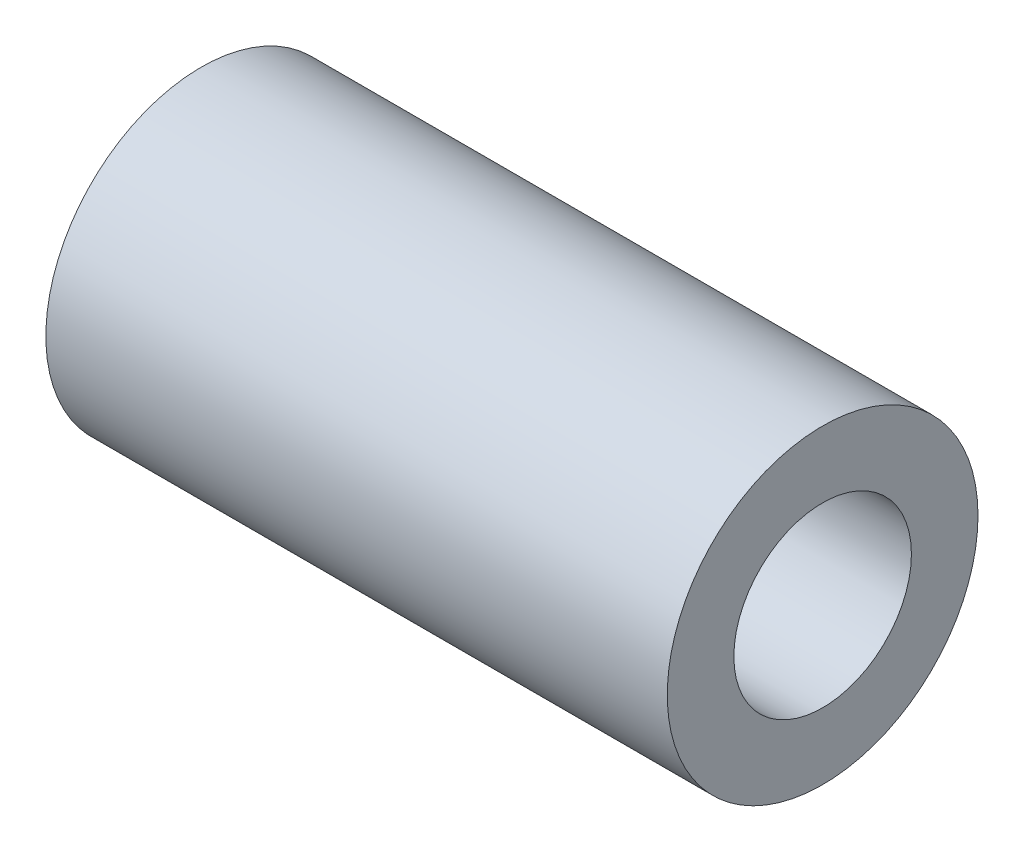
SolidWorks part; units mm, degrees
material "Brass"
ref_plane "Front Plane" through (0, 0, 0) normal (0, 0, 1) x (1, 0, 0)
ref_plane "Top Plane" through (0, 0, 0) normal (0, 1, 0) x (1, 0, 0)
ref_plane "Right Plane" through (0, 0, 0) normal (1, 0, 0) x (0, 0, -1)
sketch "Sketch2" plane through (0, 0, 0) normal (1, 0, 0) x (0, 0, -1)
  circle A0 centre (0, 0) radius 4
  circle A1 centre (0, 0) radius 7
  dimension "D1" = 14
  dimension "D2" = 8
extrude "Boss-Extrude1" add sketch "Sketch2" against normal blind 28
